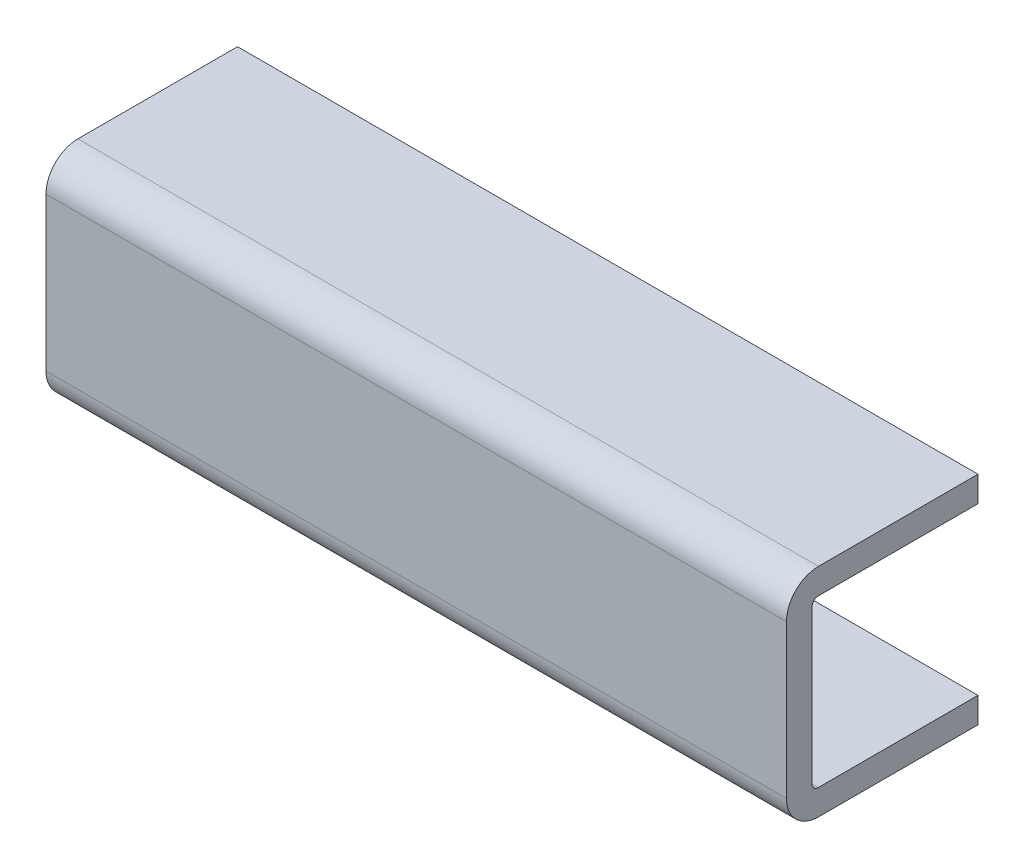
SolidWorks part; units mm, degrees
ref_plane "Front Plane" through (0, 0, 0) normal (0, 0, 1) x (1, 0, 0)
ref_plane "Top Plane" through (0, 0, 0) normal (0, 1, 0) x (1, 0, 0)
ref_plane "Right Plane" through (0, 0, 0) normal (1, 0, 0) x (0, 0, -1)
sketch "Sketch1" plane through (0, 0, 0) normal (0, 0, 1) x (1, 0, 0)
  line L0 (-92.075, 0) -> (92.075, 0) construction
  line L1 (-92.075, 26.9875) -> (92.075, 26.9875)
  line L2 (-92.075, 26.9875) -> (-92.075, -26.9875)
  line L3 (-92.075, -26.9875) -> (92.075, -26.9875)
  line L4 (92.075, 26.9875) -> (92.075, -26.9875)
  line L5 (0, 20.6375) -> (0, -20.6375) construction
  dimension "D1" = 53.975
  dimension "A" = 184.15
  dimension "B" = 41.275
extrude "Boss-Extrude1" add sketch "Sketch1" along normal mid plane 47.625
fillet "Fillet1" radius 7.9375 2 edges at (0, -26.9875, 23.8125) (0, 26.9875, 23.8125)
shell "Shell1" thickness 6.35
sketch "Sketch2" plane through (0, 0, 23.8125) normal (0, 0, 1) x (1, 0, 0)
  line L0 (-92.075, 0) -> (92.075, 0) construction
  line L1 (-92.075, 19.05) -> (-92.075, -19.05) construction
  line L2 (92.075, -19.05) -> (92.075, 19.05) construction
  circle A0 centre (-71.4375, 0) radius 7.1438
  circle A1 centre (-23.8125, 0) radius 7.1438
  circle A2 centre (23.8125, 0) radius 7.1438
  circle A3 centre (71.4375, 0) radius 7.1438
  dimension "Hole Size" = 14.2875
  dimension "Spacing" = 47.625
  dimension "D3" = 47.625
  dimension "D4" = 47.625
  dimension "D5" = 23.8125
extrude "Cut-Extrude1" [suppressed] cut sketch "Sketch2" against normal blind 47.625
equation "\"D1@Sketch1\" = (\"Thickness@Shell1\"*2)+1.625"
equation "\"D1@Boss-Extrude1\" = \"B@Sketch1\"+\"Thickness@Shell1\""
equation "\"D4@Sketch2\" = \"Spacing@Sketch2\""
equation "\"D3@Sketch2\" = \"Spacing@Sketch2\""
equation "\"D5@Sketch2\" = \"Spacing@Sketch2\"/2"
